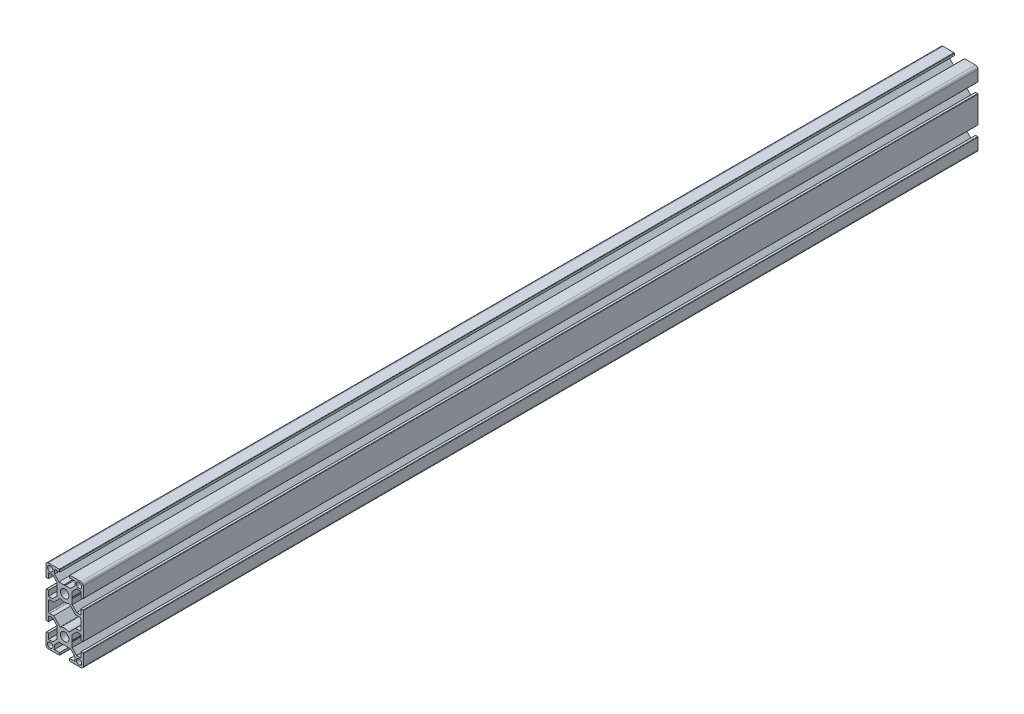
SolidWorks part; units mm, degrees
ref_plane "Front Plane" through (0, 0, 0) normal (0, 0, 1) x (1, 0, 0)
ref_plane "Top Plane" through (0, 0, 0) normal (0, 1, 0) x (1, 0, 0)
ref_plane "Right Plane" through (0, 0, 0) normal (1, 0, 0) x (0, 0, -1)
sketch "Sketch2" plane through (0, 0, 0) normal (0, 0, 1) x (1, 0, 0)
  line L0 (-13, -30) -> (-4.3, -30)
  line L1 (-4, -29.7) -> (-4, -28)
  line L2 (-4, -28) -> (-8.25, -28)
  line L3 (-8.25, -28) -> (-8.25, -24.6642)
  line L4 (-8.25, -24.6642) -> (-4.5858, -21)
  line L5 (-4.5858, -21) -> (-0.5196, -21)
  line L6 (-0.5196, -21) -> (0, -20.7)
  line L7 (0, -20.7) -> (0.5196, -21)
  line L8 (0.5196, -21) -> (4.5858, -21)
  line L9 (4.5858, -21) -> (8.25, -24.6642)
  line L10 (8.25, -24.6642) -> (8.25, -28)
  line L11 (8.25, -28) -> (4, -28)
  line L12 (4, -28) -> (4, -29.7)
  line L13 (4.3, -30) -> (13, -30)
  line L14 (15, -28) -> (15, -19.3)
  line L15 (14.7, -19) -> (13, -19)
  line L16 (13, -19) -> (13, -23.25)
  line L17 (13, -23.25) -> (9.6642, -23.25)
  line L18 (9.6642, -23.25) -> (6, -19.5858)
  line L19 (6, -19.5858) -> (6, -15.5196)
  line L20 (6, -15.5196) -> (5.7, -15)
  line L21 (5.7, -15) -> (6, -14.4804)
  line L22 (6, -14.4804) -> (6, -10.4142)
  line L23 (6, -10.4142) -> (9.6642, -6.75)
  line L24 (9.6642, -6.75) -> (13, -6.75)
  line L25 (13, -6.75) -> (13, -11)
  line L26 (13, -11) -> (14.7, -11)
  line L27 (15, -10.7) -> (15, 10.7)
  line L28 (14.7, 11) -> (13, 11)
  line L29 (13, 11) -> (13, 6.75)
  line L30 (13, 6.75) -> (9.6642, 6.75)
  line L31 (9.6642, 6.75) -> (6, 10.4142)
  line L32 (6, 10.4142) -> (6, 14.4804)
  line L33 (6, 14.4804) -> (5.7, 15)
  line L34 (5.7, 15) -> (6, 15.5196)
  line L35 (6, 15.5196) -> (6, 19.5858)
  line L36 (6, 19.5858) -> (9.6642, 23.25)
  line L37 (9.6642, 23.25) -> (13, 23.25)
  line L38 (13, 23.25) -> (13, 19)
  line L39 (13, 19) -> (14.7, 19)
  line L40 (15, 19.3) -> (15, 28)
  line L41 (13, 30) -> (4.3, 30)
  line L42 (4, 29.7) -> (4, 28)
  line L43 (4, 28) -> (8.25, 28)
  line L44 (8.25, 28) -> (8.25, 24.6642)
  line L45 (8.25, 24.6642) -> (4.5858, 21)
  line L46 (4.5858, 21) -> (0.5196, 21)
  line L47 (0.5196, 21) -> (0, 20.7)
  line L48 (0, 20.7) -> (-0.5196, 21)
  line L49 (-0.5196, 21) -> (-4.5858, 21)
  line L50 (-4.5858, 21) -> (-8.25, 24.6642)
  line L51 (-8.25, 24.6642) -> (-8.25, 28)
  line L52 (-8.25, 28) -> (-4, 28)
  line L53 (-4, 28) -> (-4, 29.7)
  line L54 (-4.3, 30) -> (-13, 30)
  line L55 (-15, 28) -> (-15, 19.3)
  line L56 (-14.7, 19) -> (-13, 19)
  line L57 (-13, 19) -> (-13, 23.25)
  line L58 (-13, 23.25) -> (-9.6642, 23.25)
  line L59 (-9.6642, 23.25) -> (-6, 19.5858)
  line L60 (-6, 19.5858) -> (-6, 15.5196)
  line L61 (-6, 15.5196) -> (-5.7, 15)
  line L62 (-5.7, 15) -> (-6, 14.4804)
  line L63 (-6, 14.4804) -> (-6, 10.4142)
  line L64 (-6, 10.4142) -> (-9.6642, 6.75)
  line L65 (-9.6642, 6.75) -> (-13, 6.75)
  line L66 (-13, 6.75) -> (-13, 11)
  line L67 (-13, 11) -> (-14.7, 11)
  line L68 (-15, 10.7) -> (-15, -10.7)
  line L69 (-14.7, -11) -> (-13, -11)
  line L70 (-13, -11) -> (-13, -6.75)
  line L71 (-13, -6.75) -> (-9.6642, -6.75)
  line L72 (-9.6642, -6.75) -> (-6, -10.4142)
  line L73 (-6, -10.4142) -> (-6, -14.4804)
  line L74 (-6, -14.4804) -> (-5.7, -15)
  line L75 (-5.7, -15) -> (-6, -15.5196)
  line L76 (-6, -15.5196) -> (-6, -19.5858)
  line L77 (-6, -19.5858) -> (-9.6642, -23.25)
  line L78 (-9.6642, -23.25) -> (-13, -23.25)
  line L79 (-13, -23.25) -> (-13, -19)
  line L80 (-13, -19) -> (-14.7, -19)
  line L81 (-15, -19.3) -> (-15, -28)
  line L82 (-13, 3.75) -> (-13, -3.75)
  line L83 (-12, -4.75) -> (-8.8358, -4.75)
  line L84 (-8.8358, -4.75) -> (-3.6518, -9.934)
  line L85 (3.6518, -9.934) -> (8.8358, -4.75)
  line L86 (8.8358, -4.75) -> (12, -4.75)
  line L87 (13, -3.75) -> (13, 3.75)
  line L88 (12, 4.75) -> (8.8358, 4.75)
  line L89 (8.8358, 4.75) -> (3.6518, 9.934)
  line L90 (-3.6518, 9.934) -> (-8.8358, 4.75)
  line L91 (-8.8358, 4.75) -> (-12, 4.75)
  arc A0 (-15, -28) -> (-13, -30) centre (-13, -28) ccw
  arc A1 (-4.3, -30) -> (-4, -29.7) centre (-4.3, -29.7) ccw
  arc A2 (4, -29.7) -> (4.3, -30) centre (4.3, -29.7) ccw
  arc A3 (13, -30) -> (15, -28) centre (13, -28) ccw
  arc A4 (15, -19.3) -> (14.7, -19) centre (14.7, -19.3) ccw
  arc A5 (14.7, -11) -> (15, -10.7) centre (14.7, -10.7) ccw
  arc A6 (15, 10.7) -> (14.7, 11) centre (14.7, 10.7) ccw
  arc A7 (14.7, 19) -> (15, 19.3) centre (14.7, 19.3) ccw
  arc A8 (15, 28) -> (13, 30) centre (13, 28) ccw
  arc A9 (4.3, 30) -> (4, 29.7) centre (4.3, 29.7) ccw
  arc A10 (-4, 29.7) -> (-4.3, 30) centre (-4.3, 29.7) ccw
  arc A11 (-13, 30) -> (-15, 28) centre (-13, 28) ccw
  arc A12 (-15, 19.3) -> (-14.7, 19) centre (-14.7, 19.3) ccw
  arc A13 (-14.7, 11) -> (-15, 10.7) centre (-14.7, 10.7) ccw
  arc A14 (-15, -10.7) -> (-14.7, -11) centre (-14.7, -10.7) ccw
  arc A15 (-14.7, -19) -> (-15, -19.3) centre (-14.7, -19.3) ccw
  circle A16 centre (11.625, 26.625) radius 2.1
  circle A17 centre (11.625, -26.625) radius 2.1
  circle A18 centre (0, -15) radius 3.4
  circle A19 centre (0, 15) radius 3.4
  arc A20 (-13, -3.75) -> (-12, -4.75) centre (-12, -3.75) ccw
  arc A21 (-3.6518, -9.934) -> (-3.2759, -9.9732) centre (-3.4397, -9.7219) ccw
  arc A22 (-3.2759, -9.9732) -> (3.2759, -9.9732) centre (0, -15) cw
  arc A23 (3.2759, -9.9732) -> (3.6518, -9.934) centre (3.4397, -9.7219) ccw
  arc A24 (12, -4.75) -> (13, -3.75) centre (12, -3.75) ccw
  arc A25 (13, 3.75) -> (12, 4.75) centre (12, 3.75) ccw
  arc A26 (3.6518, 9.934) -> (3.2759, 9.9732) centre (3.4397, 9.7219) ccw
  arc A27 (3.2759, 9.9732) -> (-3.2759, 9.9732) centre (0, 15) cw
  arc A28 (-3.2759, 9.9732) -> (-3.6518, 9.934) centre (-3.4397, 9.7219) ccw
  arc A29 (-12, 4.75) -> (-13, 3.75) centre (-12, 3.75) ccw
  circle A30 centre (-11.625, 26.625) radius 2.1
  circle A31 centre (-11.625, -26.625) radius 2.1
extrude "Boss-Extrude1" add sketch "Sketch2" along normal blind 720
